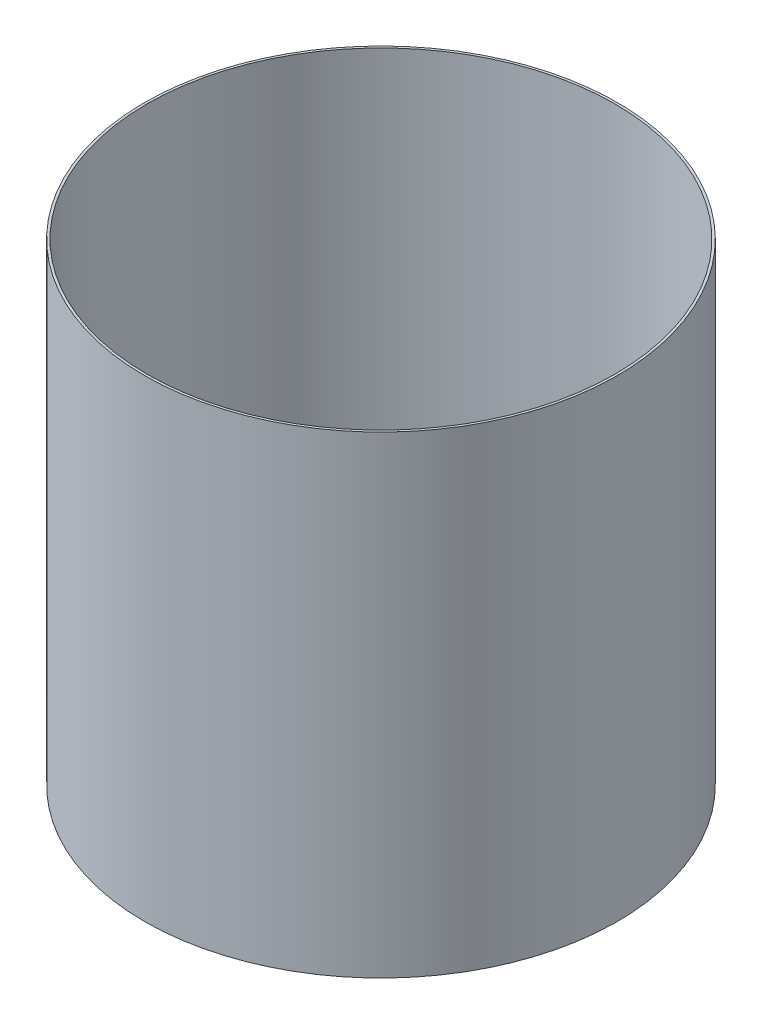
SolidWorks part; units mm, degrees
ref_plane "Front Plane" through (0, 0, 0) normal (0, 0, 1) x (1, 0, 0)
ref_plane "Top Plane" through (0, 0, 0) normal (0, 1, 0) x (1, 0, 0)
ref_plane "Right Plane" through (0, 0, 0) normal (1, 0, 0) x (0, 0, -1)
sketch "Sketch1" plane through (0, 0, 0) normal (0, 1, 0) x (1, 0, 0)
  circle A0 centre (0, 0) radius 99
  circle A1 centre (0, 0) radius 100
  dimension "D1" = 198
  dimension "D2" = 200
extrude "Boss-Extrude1" add sketch "Sketch1" along normal blind 200
